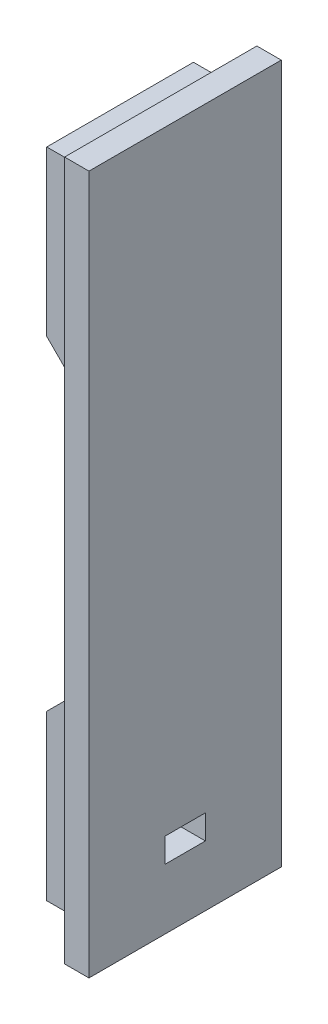
SolidWorks part; units mm, degrees
ref_plane "Front Plane" through (0, 0, 0) normal (0, 0, 1) x (1, 0, 0)
ref_plane "Top Plane" through (0, 0, 0) normal (0, 1, 0) x (1, 0, 0)
ref_plane "Right Plane" through (0, 0, 0) normal (1, 0, 0) x (0, 0, -1)
sketch "Sketch1" plane through (0, 0, 0) normal (1, 0, 0) x (0, 0, -1)
  line L1 (-11.8333, -43) -> (11.8333, -43)
  line L2 (-11.8333, -43) -> (-11.8333, 43)
  line L3 (-11.8333, 43) -> (11.8333, 43)
  line L4 (11.8333, -43) -> (11.8333, 43)
  line L5 (-11.8333, -43) -> (11.8333, 43) construction
  line L6 (-11.8333, 43) -> (11.8333, -43) construction
  point P0 (0, 0)
extrude "Boss-Extrude1" add sketch "Sketch1" along normal blind 3
sketch "Sketch2" plane through (3, 0, 0) normal (1, 0, 0) x (0, 0, -1)
  line L0 (0, 0) -> (0, -60.8438) construction
  line L1 (-2.5, -35.561) -> (2.5, -35.561)
  line L2 (-2.5, -35.561) -> (-2.5, -32.561)
  line L3 (-2.5, -32.561) -> (2.5, -32.561)
  line L4 (2.5, -35.561) -> (2.5, -32.561)
  line L5 (-2.5, -35.561) -> (2.5, -32.561) construction
  line L6 (-2.5, -32.561) -> (2.5, -35.561) construction
  point P0 (0, -34.061)
extrude "Cut-Extrude1" cut sketch "Sketch2" against normal through all
sketch "Sketch3" plane through (0, 0, 0) normal (-1, 0, 0) x (0, 0, 1)
  line L1 (-9.0271, -40.1707) -> (9.0271, -40.1707)
  line L2 (-9.0271, -40.1707) -> (-9.0271, 40.1707)
  line L3 (-9.0271, 40.1707) -> (9.0271, 40.1707)
  line L4 (9.0271, -40.1707) -> (9.0271, 40.1707)
  line L5 (-9.0271, -40.1707) -> (9.0271, 40.1707) construction
  line L6 (-9.0271, 40.1707) -> (9.0271, -40.1707) construction
  point P0 (0, 0)
extrude "Boss-Extrude2" add sketch "Sketch3" along normal blind 5
sketch "Sketch5" plane through (-5, 0, 0) normal (-1, 0, 0) x (0, 0, 1)
  line L1 (-5.9579, -38.0042) -> (5.9579, -38.0042)
  line L2 (-5.9579, -38.0042) -> (-5.9579, 38.0042)
  line L3 (-5.9579, 38.0042) -> (5.9579, 38.0042)
  line L4 (5.9579, -38.0042) -> (5.9579, 38.0042)
  line L5 (-5.9579, -38.0042) -> (5.9579, 38.0042) construction
  line L6 (-5.9579, 38.0042) -> (5.9579, -38.0042) construction
  point P0 (0, 0)
extrude "Cut-Extrude2" cut sketch "Sketch5" against normal blind 5
sketch "Sketch6" plane through (0, 0, 0) normal (0, 0, 1) x (1, 0, 0)
  line L0 (-5, -40.1707) -> (-5, 40.1707) construction
  line L1 (-5, -19.9742) -> (-1.7149, -16.6891)
  line L3 (-5, 19.9742) -> (-1.7149, 16.6891)
  line L4 (-1.7149, -16.6891) -> (-1.7149, 16.6891)
  line L7 (-5, 19.9742) -> (-5, -19.9742)
  point P0 (-5, 0)
  point P2 (-5, 0)
  dimension "D1" = 45
  dimension "D2" = 45
extrude "Cut-Extrude3" cut sketch "Sketch6" against normal through all and the other way through all
sketch "Sketch7" plane through (0, 0, 0) normal (-1, 0, 0) x (0, 0, 1)
  line L1 (-1, -4.5) -> (1, -4.5)
  line L2 (-1, -4.5) -> (-1, 4.5)
  line L3 (-1, 4.5) -> (1, 4.5)
  line L4 (1, -4.5) -> (1, 4.5)
  line L5 (-1, -4.5) -> (1, 4.5) construction
  line L6 (-1, 4.5) -> (1, -4.5) construction
  point P0 (0, 0)
extrude "Boss-Extrude3" add sketch "Sketch7" along normal blind 5
sketch "Sketch8" plane through (0, 0, 1) normal (0, 0, 1) x (1, 0, 0)
  line L4 (0, -4.5) -> (0, 4.5)
  line L5 (0, 4.5) -> (-5, 4.5)
  line L6 (-5, 4.5) -> (-5, -4.5)
  line L7 (-5, -4.5) -> (0, -4.5)
  line L8 (0, -4.5) -> (0, 4.5)
  line L9 (0, 4.5) -> (-5, 4.5)
  line L10 (-5, 4.5) -> (-5, -4.5)
  line L11 (-5, -4.5) -> (0, -4.5)
  circle A0 centre (-2.5106, 0) radius 2.5315
  arc A1 (-5, -3.7487) -> (0, -3.7345) centre (-2.5106, 0) ccw
  arc A2 (0, 3.7345) -> (-5, 3.7487) centre (-2.5106, 0) ccw
  line M5 (0, -4.5) -> (0, 4.5)
  line M6 (0, 4.5) -> (-5, 4.5)
  line M7 (-5, 4.5) -> (-5, -4.5)
  line M8 (-5, -4.5) -> (0, -4.5)
  dimension "D1" = 0
extrude "Cut-Extrude4" cut sketch "Sketch8" against normal blind 5 contours L8 A0 L10 | A1 L10 M8 | A1 L11 M5 | A2 L8 M6 | A2 L9 M7
sketch "Sketch9" plane through (-5, 0, 0) normal (-1, 0, 0) x (0, 0, 1)
  line L1 (-1.2672, -1) -> (1.2672, -1)
  line L2 (-1.2672, -1) -> (-1.2672, 1)
  line L3 (-1.2672, 1) -> (1.2672, 1)
  line L4 (1.2672, -1) -> (1.2672, 1)
  line L5 (-1.2672, -1) -> (1.2672, 1) construction
  line L6 (-1.2672, 1) -> (1.2672, -1) construction
  point P0 (0, 0)
extrude "Cut-Extrude5" cut sketch "Sketch9" against normal blind 1
sketch "Sketch10" plane through (0, 0, 1) normal (0, 0, 1) x (1, 0, 0)
  line L0 (0, 0) -> (-0.2501, 0) construction
  line L1 (0, 0) -> (-7.6994, 0) construction
  line L2 (0.632, -1.1448) -> (-0.193, -4.4539)
  line L3 (-4.4199, -0.7392) -> (-4.336, -0.6668)
  line L4 (-5.0479, -3.258) -> (-4.4199, -0.7392)
  line L8 (-5.0479, 3.258) -> (-4.4199, 0.7392)
  line L9 (-4.4199, 0.7392) -> (-4.336, 0.6668)
  line L10 (0.632, 1.1448) -> (-0.193, 4.4539)
  arc A0 (-0.193, -4.4539) -> (-5.0479, -3.258) centre (-1.7256, -0.2229) cw
  arc A1 (0.632, -1.1448) -> (-4.336, -0.6668) centre (-1.8112, -0.4824) cw
  arc A4 (0.632, 1.1448) -> (-4.336, 0.6668) centre (-1.8112, 0.4824) ccw
  arc A5 (-0.193, 4.4539) -> (-5.0479, 3.258) centre (-1.7256, 0.2229) ccw
sketch "Sketch12" plane through (0, 0, 1) normal (0, 0, 1) x (1, 0, 0)
  line L3 (-4.8362, -1) -> (-5, -1)
  line L4 (-5, -1) -> (-5, -3.7487)
  line L5 (0, -3.7345) -> (0, -0.3242)
  line L6 (-4.8362, -1) -> (-5, -1)
  line L7 (-5, -1) -> (-5, -3.7487)
  line L8 (0, -3.7345) -> (0, -0.3242)
  line L9 (-5, 3.7487) -> (-5, 1)
  line L10 (-5, 1) -> (-4.8362, 1)
  line L11 (0, 0.3242) -> (0, 3.7345)
  line L12 (-5, 3.7487) -> (-5, 1)
  line L13 (-5, 1) -> (-4.8362, 1)
  line L14 (0, 0.3242) -> (0, 3.7345)
  arc A2 (-4.8362, -1) -> (0, -0.3242) centre (-2.5106, 0) ccw
  arc A3 (-4.8362, -1) -> (0, -0.3242) centre (-2.5106, 0) ccw
  arc A6 (-5, -3.7487) -> (0, -3.7345) centre (-2.5106, 0) ccw
  arc A7 (-5, -3.7487) -> (0, -3.7345) centre (-2.5106, 0) ccw
  arc A10 (0, 0.3242) -> (-4.8362, 1) centre (-2.5106, 0) ccw
  arc A11 (0, 0.3242) -> (-4.8362, 1) centre (-2.5106, 0) ccw
  arc A12 (0, 3.7345) -> (-5, 3.7487) centre (-2.5106, 0) ccw
  arc A13 (0, 3.7345) -> (-5, 3.7487) centre (-2.5106, 0) ccw
  dimension "D1" = 0
  dimension "D2" = 0
extrude "Cut-Extrude6" cut sketch "Sketch12" against normal blind 2
extrude "Boss-Extrude5" add sketch "Sketch10" against normal blind 2
sketch "Sketch13" plane through (0, 0, -1) normal (0, 0, -1) x (-1, 0, 0)
  line L0 (0.193, 4.4539) -> (-0.6174, 4.2448)
  line L1 (0.193, -4.4539) -> (-0.7391, -4.0793)
  line L2 (-0.6174, 4.2448) -> (-0.7391, -4.0793)
  line L3 (0, -3.6798) -> (0, 3.6798)
  line L4 (0.193, 4.4539) -> (0, 3.6798)
  line L5 (0, 3.6798) -> (0, 2.251)
  line L6 (4.336, 0.6668) -> (4.4199, 0.7392)
  line L7 (4.4199, 0.7392) -> (5.0479, 3.258)
  line L9 (0, 3.6798) -> (0, 2.251)
  line L10 (4.336, 0.6668) -> (4.4199, 0.7392)
  line L11 (4.4199, 0.7392) -> (5.0479, 3.258)
  line L12 (0, -2.251) -> (0, -3.6798)
  line L13 (0, -3.6798) -> (0.193, -4.4539)
  line L14 (5.0479, -3.258) -> (4.4199, -0.7392)
  line L15 (4.4199, -0.7392) -> (4.336, -0.6668)
  line L16 (0, -2.251) -> (0, -3.6798)
  line L18 (5.0479, -3.258) -> (4.4199, -0.7392)
  line L19 (4.4199, -0.7392) -> (4.336, -0.6668)
  line L21 (0.193, 4.4539) -> (-0.6174, 4.2448)
  line L22 (-0.7391, -4.0793) -> (0.193, -4.4539)
  line L23 (0, -3.6798) -> (0, 3.6798)
  line L25 (0, -3.6798) -> (0, 3.6798)
  line L26 (-0.6174, 4.2448) -> (0.193, 4.4539)
  line L27 (0, 3.6798) -> (0, -3.6798)
  line L28 (0.193, -4.4539) -> (-0.7391, -4.0793)
  line L29 (0.193, 4.4539) -> (0, 3.6798)
  line L30 (0, -3.6798) -> (0.193, -4.4539)
  arc A2 (4.336, 0.6668) -> (0, 2.251) centre (1.8112, 0.4824) ccw
  arc A3 (5.0479, 3.258) -> (0.193, 4.4539) centre (1.7256, 0.2229) ccw
  arc A6 (0.193, -4.4539) -> (5.0479, -3.258) centre (1.7256, -0.2229) ccw
  arc A7 (0, -2.251) -> (4.336, -0.6668) centre (1.8112, -0.4824) ccw
  line M13 (0, -2.251) -> (0, -3.6798)
  line M14 (0, -3.6798) -> (0.193, -4.4539)
  dimension "D1" = 0
  dimension "D2" = 0
extrude "Boss-Extrude6" add sketch "Sketch13" against normal blind 2 contours L29 L0 L2 L1 L3 M14 M13
sketch "Sketch15" plane through (0, 0, -1) normal (0, 0, -1) x (-1, 0, 0)
  line L0 (0, 0) -> (6.6968, 0) construction
  line L1 (5.0479, 3.258) -> (4.0385, 1.6855)
  line L2 (4.0385, 1.6855) -> (4.7339, 1.6855)
  line L3 (4.0385, 1.6855) -> (4.0385, -1.6855)
  line L4 (0.193, 4.4539) -> (0, 4.4041)
  line L5 (0, 4.4041) -> (0, 2.251)
  line L6 (4.336, 0.6668) -> (4.4199, 0.7392)
  line L7 (4.4199, 0.7392) -> (5.0479, 3.258)
  line L8 (0.193, 4.4539) -> (0, 4.4041)
  line L9 (0, 4.4041) -> (0, 2.251)
  line L10 (4.336, 0.6668) -> (4.4199, 0.7392)
  line L11 (4.4199, 0.7392) -> (5.0479, 3.258)
  line L12 (0, -2.251) -> (0, -4.3763)
  line L13 (0, -4.3763) -> (0.193, -4.4539)
  line L14 (5.0479, -3.258) -> (4.4199, -0.7392)
  line L15 (4.4199, -0.7392) -> (4.336, -0.6668)
  line L16 (0, -2.251) -> (0, -4.3763)
  line L17 (0, -4.3763) -> (0.193, -4.4539)
  line L18 (5.0479, -3.258) -> (4.4199, -0.7392)
  line L19 (4.4199, -0.7392) -> (4.336, -0.6668)
  line L20 (4.0385, -1.6855) -> (4.7339, -1.6855)
  line L21 (4.7339, 1.6855) -> (4.7339, -1.6855)
  line L22 (4.0385, 1.6855) -> (4.7339, -1.6855) construction
  line L23 (4.0385, -1.6855) -> (4.7339, 1.6855) construction
  line L24 (5.0479, -3.258) -> (4.0385, -1.6855)
  arc A1 (0, -2.251) -> (4.336, -0.6668) centre (1.8112, -0.4824) ccw construction
  arc A2 (5.0479, 3.258) -> (0.193, 4.4539) centre (1.7256, 0.2229) ccw
  arc A3 (4.336, 0.6668) -> (0, 2.251) centre (1.8112, 0.4824) ccw
  arc A4 (5.0479, 3.258) -> (0.193, 4.4539) centre (1.7256, 0.2229) ccw
  arc A5 (4.336, 0.6668) -> (0, 2.251) centre (1.8112, 0.4824) ccw
  arc A6 (0.193, -4.4539) -> (5.0479, -3.258) centre (1.7256, -0.2229) ccw
  arc A7 (0, -2.251) -> (4.336, -0.6668) centre (1.8112, -0.4824) ccw
  arc A8 (0.193, -4.4539) -> (5.0479, -3.258) centre (1.7256, -0.2229) ccw
  arc A9 (0, -2.251) -> (4.336, -0.6668) centre (1.8112, -0.4824) ccw
  arc A10 (4.336, 0.6668) -> (0, 2.251) centre (1.8112, 0.4824) ccw construction
  point P8 (4.3862, 0)
  arc M21 (0, 2.251) -> (4.336, 0.6668) centre (1.8112, 0.4824) cw
  line M22 (4.336, 0.6668) -> (4.4199, 0.7392)
  line M23 (4.4199, 0.7392) -> (5.0479, 3.258)
  dimension "D1" = 0
  dimension "D2" = 0
extrude "Cut-Extrude7" cut sketch "Sketch15" against normal blind 2 contours L1 L2 M23 | L2 M21 M22 M23 | A9 L20 L18 L19 | L24 L18 L20
